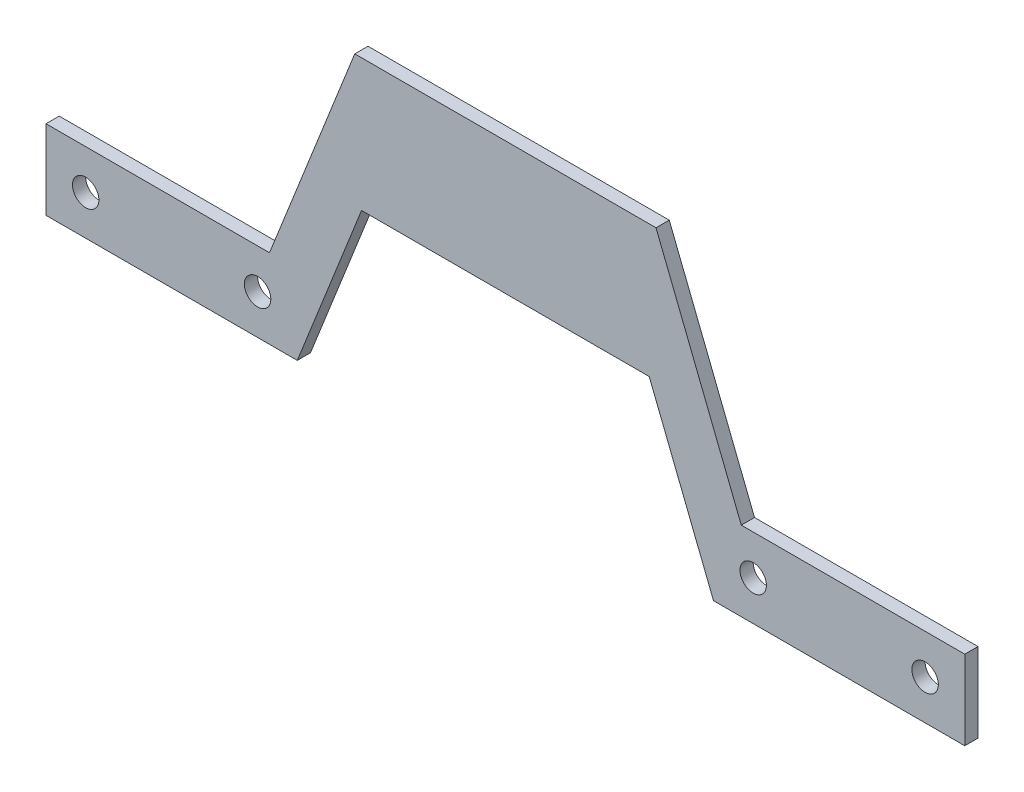
SolidWorks part; units mm, degrees
material "Placa de circuito de energia"
ref_plane "Plano frontal" through (0, 0, 0) normal (0, 0, 1) x (1, 0, 0)
ref_plane "Plano superior" through (0, 0, 0) normal (0, 1, 0) x (1, 0, 0)
ref_plane "Plano direito" through (0, 0, 0) normal (1, 0, 0) x (0, 0, -1)
sketch "Esboço1" plane through (0, 0, 0) normal (0, 0, 1) x (1, 0, 0)
  line L15 (0, 0) -> (0, 39.3505) construction
  line L16 (0, 0) -> (0.5698, -43.1535) construction
  line L17 (0.0666, -5.045) -> (-21.7521, -5.045)
  line L18 (-21.7521, -5.045) -> (-31.4765, -29.545)
  line L19 (-31.4765, -29.545) -> (-69.4765, -29.545)
  line L20 (-69.4765, -29.545) -> (-69.4765, -17.545)
  line L21 (-69.4765, -17.545) -> (-35.6783, -17.545)
  line L22 (-35.6783, -17.545) -> (-22.7785, 14.955)
  line L23 (-22.7785, 14.955) -> (22.7785, 14.955)
  line L24 (-0.0666, -5.045) -> (21.7521, -5.045)
  line L25 (35.6783, -17.545) -> (22.7785, 14.955)
  line L26 (69.4765, -17.545) -> (35.6783, -17.545)
  line L27 (69.4765, -29.545) -> (69.4765, -17.545)
  line L28 (31.4765, -29.545) -> (69.4765, -29.545)
  line L29 (21.7521, -5.045) -> (31.4765, -29.545)
  circle A0 centre (-63.4765, -23.545) radius 2
  circle A1 centre (-37.4765, -23.545) radius 2
  circle A2 centre (37.4765, -23.545) radius 2
  circle A3 centre (63.4765, -23.545) radius 2
  point P21 (0, 14.955)
  dimension "D5" = 4
  dimension "D1" = 20
  dimension "D2" = 12
  dimension "D3" = 38
  dimension "D4" = 24.5
  dimension "D6" = 6
  dimension "D7" = 6
  dimension "D8" = 6
  dimension "D9" = 6
  dimension "D10" = 45.557
  dimension "D11" = 43.5043
extrude "Ressalto-extrusão2" add sketch "Esboço1" along normal blind 2 contours L24 L29 L28 L27 L26 L25 L23 L22 L21 L20 L19 L18 L17 A2 A1 A0 A3
